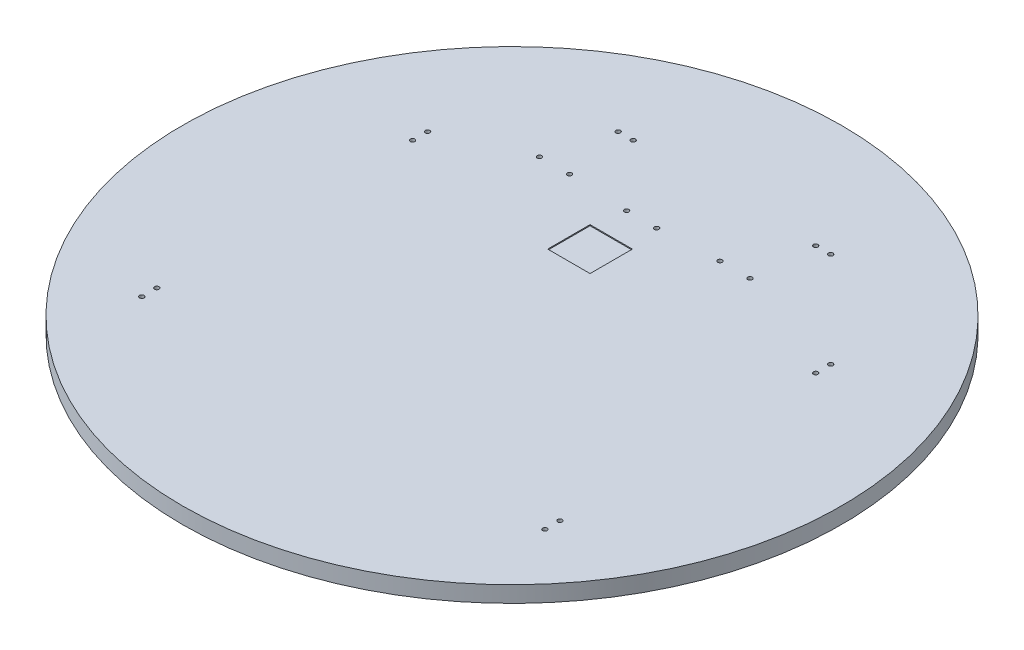
SolidWorks part; units mm, degrees
material "6061-O (SS)"
ref_plane "Front Plane" through (0, 0, 0) normal (0, 0, 1) x (1, 0, 0)
ref_plane "Top Plane" through (0, 0, 0) normal (0, 1, 0) x (1, 0, 0)
ref_plane "Right Plane" through (0, 0, 0) normal (1, 0, 0) x (0, 0, -1)
sketch "Sketch1" plane through (0, 0, 0) normal (0, 1, 0) x (1, 0, 0)
  line L0 (216.675, 455) -> (216.675, 382.6005) construction
  line L1 (0, 0) -> (433.35, 0)
  line L2 (0, 0) -> (0, 455)
  line L3 (0, 455) -> (433.35, 455)
  line L4 (433.35, 0) -> (433.35, 455)
  line L5 (433.35, 227.5) -> (378.9416, 227.5) construction
  circle A0 centre (216.675, 227.5) radius 328.6125
  dimension "D3" = 657.225
  dimension "D1" = 433.35
  dimension "D2" = 455
extrude "Boss-Extrude1" add sketch "Sketch1" along normal blind 16.1798 contours A0 L4 L1 L2 L3
sketch "Sketch2" plane through (0, 16.1798, 0) normal (0, 1, 0) x (1, 0, 0)
  line L0 (159.8566, 236.0356) -> (316.5233, 236.0356) construction
  line L1 (216.675, 455) -> (216.675, 367.0796) construction
  line L3 (0, 227.5) -> (99.072, 227.5) construction
  line L5 (288.7819, 157.0045) -> (301.6615, 145.7149)
  line L6 (179.9325, 228.0439) -> (179.9325, 219.7046)
  line L7 (172.7246, 238.9765) -> (164.5928, 238.9765)
  line L8 (291.4871, 264.3322) -> (291.4871, 255.9106)
  line L9 (433.35, 227.5) -> (378.9416, 227.5) construction
  line L10 (0, 0) -> (0, 455) construction
  spline S0 degree 3 poles (204.248, 318.6336) (205.781, 303.6716) (207.3874, 284.2748) (222.882, 276.7071) knots 0 0 0 0 1 1 1 1
  spline S1 degree 3 poles (204.248, 318.6336) (213.0934, 328.5517) (229.2045, 307.2151) (219.4326, 291.0341) (229.3323, 284.949) knots 0 0 0 0 0.526191 1 1 1 1
  spline S2 degree 3 poles (222.882, 276.7071) (218.0664, 288.7163) (222.6483, 289.6417) (229.3323, 271.899) knots 0 0 0 0 1 1 1 1
  spline S3 degree 2 poles (229.3323, 271.899) (238.1631, 242.6846) (234.444, 274.9602) knots 0 0 0 1 1 1
  spline S4 degree 2 poles (234.444, 274.9602) (228.2091, 306.8955) (229.3323, 284.949) knots 0 0 0 1 1 1
  spline S5 degree 2 poles (288.7819, 278.8458) (285.8661, 284.4945) (268.9851, 283.6061) knots 0 0 0 1 1 1
  spline S6 degree 3 poles (268.9851, 283.6061) (255.3498, 286.1365) (255.3438, 306.1838) (240.3506, 305.0726) knots 0 0 0 0 1 1 1 1
  spline S7 degree 3 poles (240.3506, 305.0726) (229.6546, 311.9956) (230.9006, 325.4605) (220.9748, 333.9103) knots 0 0 0 0 1 1 1 1
  spline S8 degree 2 poles (220.9748, 333.9103) (193.1373, 338.6225) (200.5281, 304.2998) knots 0 0 0 1 1 1
  spline S9 degree 3 poles (200.5281, 304.2998) (210.1124, 296.6041) (193.9218, 285.3728) (195.9942, 274.4319) (196.4763, 266.9593) knots 0 0 0 0 0.583048 1 1 1 1
  spline S10 degree 3 poles (196.4763, 266.9593) (196.928, 263.6309) (183.4632, 260.5292) (172.3848, 249.6087) (179.1837, 252.3658) (184.2165, 252.0811) knots 0 0 0 0 0.285101 0.753101 1 1 1 1
  spline S11 degree 3 poles (184.2165, 252.0811) (191.0126, 243.2933) (197.77, 233.1453) (193.6887, 216.0161) (195.6445, 209.2469) (197.441, 206.893) knots 0 0 0 0 0.553605 0.837568 1 1 1 1
  spline S12 degree 3 poles (197.441, 206.893) (198.6636, 204.5328) (200.297, 221.6882) (199.899, 236.2396) (205.1269, 213.5516) (206.0397, 210.7391) knots 0 0 0 0 0.304023 0.518516 1 1 1 1
  spline S13 degree 2 poles (206.0397, 210.7391) (220.5471, 187.3638) (208.6594, 211.8536) knots 0 0 0 1 1 1
  spline S14 degree 3 poles (208.6594, 211.8536) (211.2885, 226.8346) (213.0105, 228.3477) (213.5041, 256.4914) (221.5571, 243.0128) (220.9748, 238.5472) knots 0 0 0 0 0.637247 0.783173 1 1 1 1
  spline S15 degree 3 poles (220.9748, 238.5472) (221.3002, 221.5517) (247.9552, 208.554) (253.2232, 187.8293) (256.1095, 177.8763) knots 0 0 0 0 0.638947 1 1 1 1
  spline S16 degree 3 poles (256.1095, 177.8763) (268.8281, 161.349) (254.6125, 187.1882) (255.657, 206.8113) (237.4081, 217.4933) (238.0806, 231.8969) (236.7428, 236.7442) knots 0 0 0 0 0.336118 0.57659 0.76322 1 1 1 1
  spline S17 degree 3 poles (236.7428, 236.7442) (238.6322, 226.2244) (259.2198, 212.4458) (258.9874, 192.3856) (265.5478, 182.0978) knots 0 0 0 0 0.504024 1 1 1 1
  spline S18 degree 3 poles (265.5478, 182.0978) (279.2911, 170.5826) (291.9426, 168.6086) (299.4636, 154.0017) knots 0 0 0 0 1 1 1 1
  spline S19 degree 3 poles (299.4636, 154.0017) (298.7397, 156.4846) (293.2568, 176.2957) (267.012, 192.4536) (278.9459, 191.1444) (291.4871, 177.8763) knots 0 0 0 0 0.335954 0.633171 1 1 1 1
  spline S20 degree 3 poles (291.4871, 177.8763) (305.3991, 171.3985) (309.183, 147.7622) (327.3262, 148.261) knots 0 0 0 0 1 1 1 1
  spline S21 degree 3 poles (327.3262, 148.261) (314.907, 153.4001) (304.4514, 187.0094) (276.4973, 207.5506) (268.9851, 228.0439) knots 0 0 0 0 0.367968 1 1 1 1
  spline S22 degree 3 poles (268.9851, 228.0439) (275.4374, 220.2607) (289.6174, 203.637) (306.5297, 187.3843) (313.0869, 177.8763) knots 0 0 0 0 0.450948 1 1 1 1
  spline S23 degree 2 poles (313.0869, 177.8763) (306.7797, 201.0929) (291.4871, 219.7046) knots 0 0 0 1 1 1
  spline S24 degree 3 poles (291.4871, 219.7046) (306.8557, 224.8704) (309.2331, 217.2278) (316.0846, 209.342) knots 0 0 0 0 1 1 1 1
  spline S25 degree 2 poles (316.0846, 209.342) (322.6254, 212.0106) (325.823, 205.3433) knots 0 0 0 1 1 1
  spline S26 degree 3 poles (325.823, 205.3433) (328.9497, 212.5144) (313.6253, 211.9373) (315.6447, 215.9835) (307.218, 224.0865) knots 0 0 0 0 0.423119 1 1 1 1
  spline S27 degree 3 poles (307.218, 224.0865) (296.7656, 223.6566) (281.8462, 244.8092) (269.9223, 269.0071) (288.7819, 278.8458) knots 0 0 0 0 0.397886 1 1 1 1
  spline S28 degree 3 poles (268.9851, 173.1202) (264.3054, 162.452) (284.8217, 164.0635) (286.0919, 138.8866) (303.5125, 137.5721) (307.218, 130.4316) knots 0 0 0 0 0.353537 0.62059 1 1 1 1
  spline S29 degree 3 poles (307.218, 130.4316) (309.9462, 139.9294) (293.3664, 138.4293) (289.5748, 151.6504) (288.7819, 157.0045) knots 0 0 0 0 0.589021 1 1 1 1
  spline S30 degree 2 poles (268.9851, 173.1202) (289.7873, 165.166) (301.6615, 145.7149) knots 0 0 0 1 1 1
  spline S31 degree 2 poles (187.6074, 242.888) (187.2515, 233.5985) (179.9325, 228.0439) knots 0 0 0 1 1 1
  spline S32 degree 3 poles (179.9325, 219.7046) (190.1537, 209.4809) (178.0585, 194.3793) (189.8899, 184.2525) knots 0 0 0 0 1 1 1 1
  spline S33 degree 3 poles (189.8899, 184.2525) (184.3261, 190.7253) (193.0625, 203.1935) (187.9987, 213.7671) (187.6074, 219.7046) knots 0 0 0 0 0.569021 1 1 1 1
  spline S34 degree 3 poles (187.6074, 219.7046) (190.1157, 219.609) (192.2571, 209.1857) (193.2508, 212.0277) (195.2495, 227.9972) (188.3512, 240.3792) (187.6074, 242.888) knots 0 0 0 0 0.292646 0.341972 0.587289 1 1 1 1
  spline S35 degree 3 poles (172.7246, 245) (175.5453, 251.9192) (192.0636, 247.0075) (183.2658, 239.3781) knots 0 0 0 0 1 1 1 1
  spline S36 degree 3 poles (183.2658, 239.3781) (186.7274, 236.8547) (168.0791, 225.5256) (182.5735, 236.8903) (179.9325, 239.3781) knots 0 0 0 0 0.546598 1 1 1 1
  spline S37 degree 2 poles (179.9325, 239.3781) (176.1345, 242.7641) (172.7246, 238.9765) knots 0 0 0 1 1 1
  spline S38 degree 3 poles (164.5928, 238.9765) (156.1995, 239.8298) (164.2269, 220.2116) (157.0634, 235.4628) knots 0 0 0 0 1 1 1 1
  spline S39 degree 2 poles (157.0634, 235.4628) (165.1553, 241.7278) (155.6641, 240.9713) knots 0 0 0 1 1 1
  spline S40 degree 3 poles (155.6641, 240.9713) (156.0939, 241.4306) (143.6587, 231.0651) (152.3877, 246.0497) (155.1288, 244.6219) (159.0532, 246.7907) knots 0 0 0 0 0.354688 0.612004 1 1 1 1
  spline S41 degree 3 poles (159.0532, 246.7907) (164.2931, 249.1719) (167.7489, 241.9325) (172.7246, 245) knots 0 0 0 0 1 1 1 1
  spline S42 degree 2 poles (283.8472, 252.0811) (289.8845, 245.2602) (289.4799, 252.8372) knots 0 0 0 1 1 1
  spline S43 degree 3 poles (289.4799, 252.8372) (291.2332, 252.3918) (294.8881, 242.1086) (296.2084, 248.313) knots 0 0 0 0 1 1 1 1
  spline S44 degree 3 poles (296.2084, 248.313) (299.6337, 245.7284) (301.3279, 257.0767) (302.8904, 250.3174) (304.843, 249.0869) knots 0 0 0 0 0.613065 1 1 1 1
  spline S45 degree 3 poles (304.843, 249.0869) (310.4983, 245.5604) (305.0643, 259.9099) (310.2736, 250.1718) knots 0 0 0 0 1 1 1 1
  spline S46 degree 3 poles (310.2736, 250.1718) (312.4835, 244.9417) (326.5637, 235.7027) (327.3262, 224.0865) knots 0 0 0 0 1 1 1 1
  spline S47 degree 3 poles (327.3262, 224.0865) (320.4169, 229.1365) (320.5395, 235.4198) (312.1765, 238.5472) knots 0 0 0 0 1 1 1 1
  spline S48 degree 3 poles (312.1765, 238.5472) (311.2989, 238.6253) (309.6732, 238.3132) (305.3838, 239.7345) (304.6914, 245.7464) (304.1486, 240.332) (305.8913, 236.7442) knots 0 0 0 0 0.313348 0.375249 0.619013 1 1 1 1
  spline S49 degree 3 poles (305.8913, 236.7442) (310.7983, 236.4704) (316.9507, 218.5453) (313.8986, 223.6115) (308.489, 229.2377) knots 0 0 0 0 0.653464 1 1 1 1
  spline S50 degree 3 poles (308.489, 229.2377) (303.7984, 231.9983) (297.1255, 234.7201) (296.2084, 240.9713) knots 0 0 0 0 1 1 1 1
  spline S51 degree 3 poles (296.2084, 240.9713) (291.5933, 238.5458) (294.3492, 236.5732) (296.9483, 232.7431) knots 0 0 0 0 1 1 1 1
  spline S52 degree 2 poles (296.9483, 232.7431) (286.8831, 239.6216) (283.8472, 252.0811) knots 0 0 0 1 1 1
  spline S53 degree 3 poles (288.7819, 274.9602) (286.1977, 271.1413) (275.0078, 264.4827) (286.9531, 253.0636) (283.2603, 259.5334) (283.0941, 266.2259) (287.128, 266.9593) knots 0 0 0 0 0.508346 0.683079 0.815942 1 1 1 1
  spline S54 degree 3 poles (288.7819, 274.9602) (298.4228, 274.997) (309.9846, 269.2553) (308.489, 257.0061) knots 0 0 0 0 1 1 1 1
  spline S55 degree 3 poles (308.489, 257.0061) (295.7497, 278.6277) (307.3258, 258.4531) (303.4488, 252.8372) knots 0 0 0 0 1 1 1 1
  spline S56 degree 3 poles (303.4488, 252.8372) (301.4872, 256.2149) (298.1344, 275.7126) (298.656, 257.0061) knots 0 0 0 0 1 1 1 1
  spline S57 degree 3 poles (298.656, 257.0061) (294.7195, 239.098) (298.5823, 275.724) (294.7744, 260.5664) knots 0 0 0 0 1 1 1 1
  spline S58 degree 2 poles (287.128, 266.9593) (291.2093, 266.1874) (291.4871, 264.3322) knots 0 0 0 1 1 1
  spline S59 degree 2 poles (291.4871, 255.9106) (295.6731, 246.1954) (294.7744, 260.5664) knots 0 0 0 1 1 1
sketch "Sketch3" plane through (0, 16.1798, 0) normal (0, 1, 0) x (1, 0, 0)
  line L3 (0, 0) -> (433.35, 0) construction
  line L6 (433.35, 0) -> (433.35, 455) construction
  line L7 (0, 455) -> (433.35, 455) construction
  line L8 (0, 0) -> (0, 455) construction
  circle A0 centre (322.675, 439.325) radius 2.25
  circle A1 centre (307.675, 439.325) radius 2.25
  circle A2 centre (110.675, 439.325) radius 2.25
  circle A3 centre (125.675, 439.325) radius 2.25
  circle A4 centre (183.215, 375.2) radius 2.25
  circle A5 centre (213.215, 375.2) radius 2.25
  circle A6 centre (15.675, 329.325) radius 2.25
  circle A7 centre (15.675, 344.325) radius 2.25
  circle A8 centre (417.675, 329.325) radius 2.25
  circle A9 centre (417.675, 344.325) radius 2.25
  circle A10 centre (417.675, 59.325) radius 2.25
  circle A11 centre (417.675, 74.325) radius 2.25
  circle A12 centre (15.675, 59.325) radius 2.25
  circle A13 centre (15.675, 74.325) radius 2.25
  circle A14 centre (303.215, 378.325) radius 2.25
  circle A15 centre (273.215, 378.325) radius 2.25
  circle A16 centre (123.215, 378.325) radius 2.25
  circle A17 centre (93.215, 378.325) radius 2.25
  dimension "D4" = 4.5
  dimension "D1" = 15
  dimension "D3" = 59.325
  dimension "D5" = 30
  dimension "D6" = 30
  dimension "D7" = 30
  dimension "D8" = 15
  dimension "D9" = 79.8
  dimension "D10" = 15.675
  dimension "D11" = 15
  dimension "D12" = 110.675
  dimension "D13" = 183.215
  dimension "D14" = 93.215
  dimension "D15" = 76.675
  dimension "D16" = 15.675
  dimension "D17" = 110.675
  dimension "D18" = 130.135
  dimension "D19" = 76.675
  dimension "D20" = 15
  dimension "D21" = 15.675
  dimension "D22" = 110.675
  dimension "D23" = 15.675
  dimension "D24" = 110.675
  dimension "D25" = 15
  dimension "D26" = 15
  dimension "D27" = 15.675
  dimension "D28" = 59.325
  dimension "D29" = 15.675
extrude "Cut-Extrude1" cut sketch "Sketch3" against normal through all
sketch "Sketch4" plane through (0, 16.1798, 0) normal (0, 1, 0) x (1, 0, 0)
  line L1 (177, 302.75) -> (219.25, 302.75)
  line L2 (177, 302.75) -> (177, 345)
  line L3 (177, 345) -> (219.25, 345)
  line L4 (219.25, 302.75) -> (219.25, 345)
  line L6 (0, 455) -> (433.35, 455) construction
  line L7 (0, 0) -> (0, 455) construction
  dimension "D1" = 42.25
  dimension "D2" = 42.25
  dimension "D3" = 110
  dimension "D4" = 177
extrude "Cut-Extrude2" cut sketch "Sketch4" against normal blind 1
sketch "Sketch5" plane through (0, 0, 0) normal (0, -1, 0) x (1, 0, 0)
  circle A0 centre (15.675, -59.325) radius 3.75
  circle A1 centre (15.675, -74.325) radius 3.75
  circle A2 centre (15.675, -344.325) radius 3.75
  circle A3 centre (15.675, -329.325) radius 3.75
  circle A4 centre (93.215, -378.325) radius 3.75
  circle A5 centre (123.215, -378.325) radius 3.75
  circle A6 centre (183.215, -375.2) radius 3.75
  circle A7 centre (213.215, -375.2) radius 3.75
  circle A8 centre (273.215, -378.325) radius 3.75
  circle A9 centre (125.675, -439.325) radius 3.75
  circle A10 centre (110.675, -439.325) radius 3.75
  circle A11 centre (303.215, -378.325) radius 3.75
  circle A12 centre (307.675, -439.325) radius 3.75
  circle A13 centre (322.675, -439.325) radius 3.75
  circle A14 centre (417.675, -344.325) radius 3.75
  circle A15 centre (417.675, -329.325) radius 3.75
  circle A16 centre (417.675, -74.325) radius 3.75
  circle A17 centre (417.675, -59.325) radius 3.75
  dimension "D1" = 7.5
extrude "Cut-Extrude3" cut sketch "Sketch5" against normal blind 7.5
